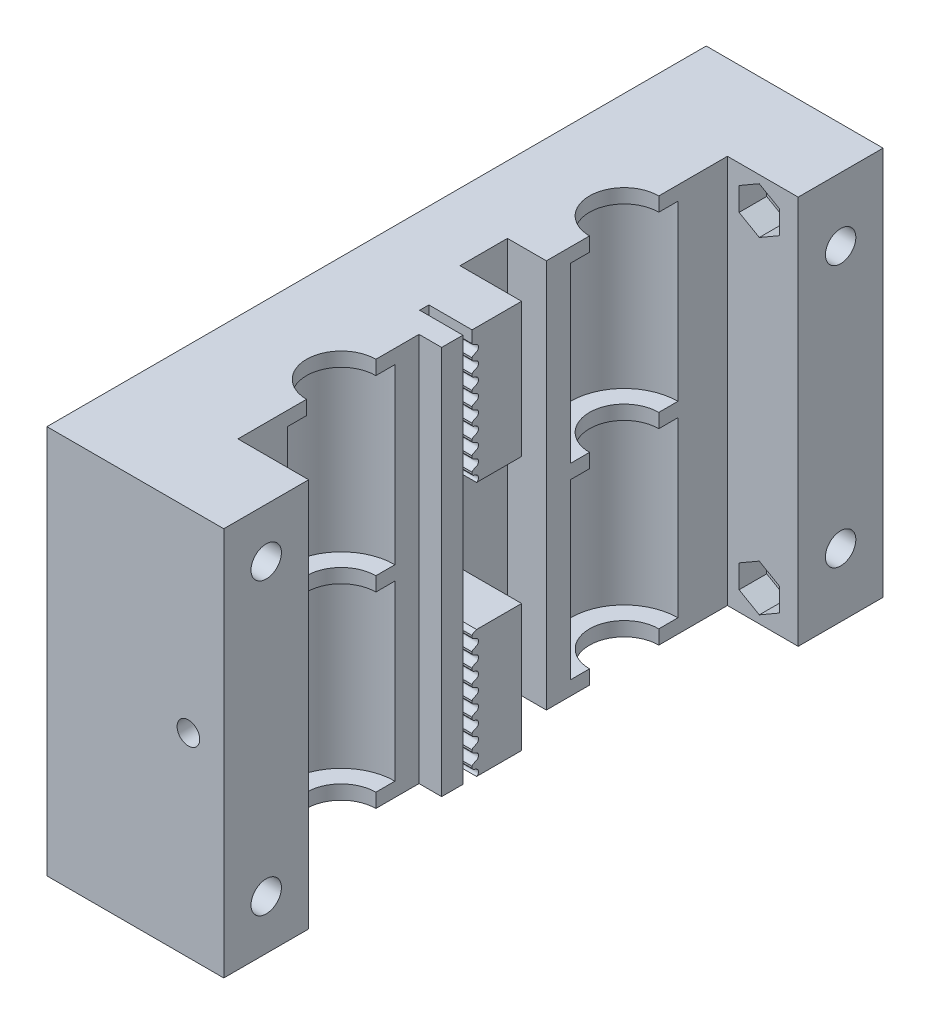
SolidWorks part; units mm, degrees
ref_plane "Front Plane" through (0, 0, 0) normal (0, 0, 1) x (1, 0, 0)
ref_plane "Top Plane" through (0, 0, 0) normal (0, 1, 0) x (1, 0, 0)
ref_plane "Right Plane" through (0, 0, 0) normal (1, 0, 0) x (0, 0, -1)
sketch "Sketch1" plane through (0, 0, 0) normal (0, 1, 0) x (1, 0, 0)
  line L0 (0, 36.6) -> (0, 43.6)
  line L1 (0, 43.6) -> (10, 43.6)
  line L2 (10, 43.6) -> (10, 55.6)
  line L3 (10, 55.6) -> (-15, 55.6)
  line L5 (-15, -37.6) -> (10, -37.6)
  line L6 (10, -37.6) -> (10, -25.6)
  line L7 (10, -25.6) -> (0, -25.6)
  line L8 (0, -25.6) -> (0, -18.6)
  line L9 (0, 21.4) -> (0, -3.4) construction
  line L10 (0, 18) -> (-5.5, 18)
  line L11 (-5.5, 18) -> (-5.5, 0)
  line L12 (-5.5, 0) -> (0, 0)
  line L24 (-15, 55.6) -> (-15, -37.6)
  line L25 (0, 0) -> (0, -3.4)
  line L26 (0, 18) -> (0, 21.4)
  arc A1 (0, 21.4) -> (0, 36.6) centre (0, 29) cw
  arc A2 (0, -18.6) -> (0, -3.4) centre (0, -11) cw
  dimension "D2" = 7.6
  dimension "D3" = 7.6
  dimension "D4" = 7
  dimension "D5" = 7
  dimension "D6" = 12
  dimension "D7" = 12
  dimension "D8" = 18
  dimension "D9" = 10
  dimension "D10" = 10
  dimension "D11" = 5.5
  dimension "D12" = 3.4
  dimension "D13" = 3.4
  dimension "D14" = 25
  dimension "D15" = 40
extrude "Boss-Extrude1" add sketch "Sketch1" along normal blind 55
sketch "Sketch2" plane through (0, 0, 0) normal (0, -1, 0) x (1, 0, 0)
  line L0 (0, 18.6) -> (0, 15.9)
  line L1 (0, 6.1) -> (0, 3.4)
  line L2 (0, -21.4) -> (0, -24.102)
  line L3 (0, -33.898) -> (0, -36.6)
  arc A0 (0, 3.4) -> (0, 18.6) centre (0, 11) cw
  arc A1 (0, 6.1) -> (0, 15.9) centre (0, 11) cw
  arc A2 (0, -36.6) -> (0, -21.4) centre (0, -29) cw
  arc A3 (0, -33.898) -> (0, -24.102) centre (0, -29) cw
  dimension "D1" = 4.9
  dimension "D2" = 4.898
extrude "Boss-Extrude2" add sketch "Sketch2" against normal blind 2
ref_plane "Plane1" through (0, 26.5, 0) normal (0, -1, 0) x (-1, 0, 0)
sketch "Sketch3" plane through (0, 26.5, 0) normal (0, -1, 0) x (-1, 0, 0)
  line L0 (0, -3.4) -> (0, -6.1)
  line L1 (0, -15.9) -> (0, -18.6)
  line L2 (0, 21.4) -> (0, 24.1)
  line L3 (0, 33.9) -> (0, 36.6)
  arc A0 (0, -18.6) -> (0, -3.4) centre (0, -11) ccw
  arc A1 (0, -15.9) -> (0, -6.1) centre (0, -11) ccw
  arc A2 (0, 36.6) -> (0, 21.4) centre (0, 29) cw
  arc A3 (0, 24.1) -> (0, 33.9) centre (0, 29) ccw
  dimension "D1" = 4.9
extrude "Boss-Extrude3" add sketch "Sketch3" against normal blind 2
ref_plane "Plane2" through (0, 53, 0) normal (0, -1, 0) x (-1, 0, 0)
sketch "Sketch4" plane through (0, 53, 0) normal (0, -1, 0) x (-1, 0, 0)
  line L0 (0, -18.6) -> (0, -15.9)
  line L1 (0, -6.1) -> (0, -3.4)
  line L2 (0, 36.6) -> (0, 33.9)
  line L3 (0, 24.1) -> (0, 21.4)
  arc A0 (0, -3.4) -> (0, -18.6) centre (0, -11) cw
  arc A1 (0, -15.9) -> (0, -6.1) centre (0, -11) ccw
  arc A2 (0, -15.9) -> (0, -6.1) centre (0, -11) ccw construction
  arc A3 (0, 21.4) -> (0, 36.6) centre (0, 29) ccw construction
  arc A5 (0, 24.1) -> (0, 33.9) centre (0, 29) ccw
  arc A6 (0, 21.4) -> (0, 36.6) centre (0, 29) ccw
  arc A7 (0, 24.1) -> (0, 33.9) centre (0, 29) ccw construction
extrude "Boss-Extrude4" add sketch "Sketch4" against normal blind 2
sketch "Sketch7" plane through (0, 55, 0) normal (0, 1, 0) x (1, 0, 0)
  line L0 (0, 0) -> (3.2, 0)
  line L1 (3.2, 0) -> (3.2, -2)
  line L2 (3.2, -2) -> (0, -2)
  line L3 (0, -6.1) -> (0, 0) construction
  line L4 (0, -2) -> (0, 0)
  dimension "D1" = 2
  dimension "D2" = 3.2
extrude "Boss-Extrude5" add sketch "Sketch7" against normal up to surface (55 mm away) up to face at (-0.6749, 0, -9)
sketch "Sketch8" plane through (0, 55, 0) normal (0, 1, 0) x (1, 0, 0)
  line L0 (0, 18) -> (0, 0) construction
  line L1 (-3.9424, 9) -> (6.0186, 9) construction
  line L2 (-5.5, 0) -> (3.2, 0)
  line L3 (3.2, 0) -> (-5.5, 0) construction
  line L4 (3.2, 0) -> (3.2, 3)
  line L5 (3.2, 3) -> (-5.5, 3)
  line L6 (-5.5, 0) -> (-5.5, 18) construction
  line L7 (-5.5, 3) -> (-5.5, 0)
  line L8 (3.2, -2) -> (3.2, 0) construction
  line L9 (-5.5, 11.3) -> (3.2, 11.3)
  line L10 (3.2, 11.3) -> (3.2, 4.3)
  line L11 (3.2, 4.3) -> (-5.5, 4.3)
  line L12 (-5.5, 4.3) -> (-5.5, 11.3)
  point P6 (0, 9)
  dimension "D1" = 3
  dimension "D2" = 7
  dimension "D3" = 1.3
extrude "Boss-Extrude6" add sketch "Sketch8" against normal up to surface (55 mm away) up to face at (-0.2443, 0, -7.7778)
sketch "Sketch11" plane through (3.2, 0, 0) normal (1, 0, 0) x (0, 0, -1)
  line L0 (1264.5675, 560.6102) -> (1262.5675, 560.6102) construction
  line L1 (4.3, 0) -> (4.3, 55) construction
  line L2 (4.2853, 45.4328) -> (4.2853, 47.4569)
  spline S0 degree 3 poles (4.2853, 47.4569) (4.284, 47.4147) (4.2867, 47.3463) (4.3158, 47.2523) (4.3712, 47.1708) (4.4771, 47.1012) (4.6041, 47.0544) (4.7214, 46.9971) (4.8254, 46.9474) (4.9241, 46.9047) (5.0186, 46.8525) (5.1086, 46.7783) (5.1561, 46.6816) (5.1905, 46.5926) (5.1913, 46.5195) (5.1931, 46.4561) (5.1891, 46.3829) (5.1871, 46.2871) (5.1399, 46.1709) (5.0494, 46.057) (4.9087, 45.9856) (4.7554, 45.916) (4.621, 45.8529) (4.5075, 45.8004) (4.4122, 45.7562) (4.3028, 45.6419) (4.2855, 45.5136) (4.2853, 45.4328) knots 0 0 0 0 0.042789 0.068472 0.09859 0.140403 0.193951 0.235463 0.272242 0.310543 0.344117 0.381404 0.42616 0.451184 0.477135 0.499165 0.515432 0.551275 0.595353 0.639476 0.695379 0.752126 0.810504 0.845135 0.878871 0.916023 1 1 1 1
  line M5 (4.3, 55) -> (4.3, 0)
  dimension "D1" = 2
extrude "Cut-Extrude4" cut sketch "Sketch11" against normal up to surface (8.7 mm away) contours S0 M5 up to face at (-5.5, 27.5, -3.65)
pattern_linear "LPattern1" count 24 spacing 2 along (0, 1, 0) count 4 spacing 2 along (0, 1, 0) of "Cut-Extrude4"
sketch "Sketch12" plane through (3.2, 0, 0) normal (1, 0, 0) x (0, 0, -1)
  line L0 (11.3, 0) -> (11.3, 55) construction
  line L1 (11.3, 36) -> (4.3, 36)
  line L2 (11.3, 36) -> (11.3, 18)
  line L3 (11.3, 18) -> (4.3, 18)
  line L4 (4.3, 36) -> (4.3, 18)
  dimension "D1" = 18
  dimension "D2" = 19
extrude "Cut-Extrude5" cut sketch "Sketch12" against normal up to surface (8.7 mm away) up to face at (-5.5, 27.5, -14.65)
sketch "Sketch13" plane through (0, 55, 0) normal (0, 1, 0) x (1, 0, 0)
  line L0 (-5.5, 3) -> (-2.9059, 3)
  line L1 (3.2, 3) -> (-5.5, 3) construction
  line L6 (-2.9059, 3) -> (-2.9059, 7.169)
  line L7 (-2.9059, 7.169) -> (-5.5, 7.169)
  line L8 (-5.5, 18) -> (-5.5, 0) construction
  line L9 (-5.5, 7.169) -> (-5.5, 3)
extrude "Boss-Extrude16" add sketch "Sketch13" against normal up to surface (55 mm away) up to face at (-0.409, 0, -8.1123)
sketch "Sketch14" plane through (0, 55, 0) normal (0, 1, 0) x (1, 0, 0)
  line L0 (0, 0) -> (0, -2)
  line L1 (0, -2) -> (3.2, -2)
  line L2 (3.2, -2) -> (3.2, 0)
  line L3 (3.2, -2) -> (3.2, 3) construction
  line L4 (3.2, 0) -> (0, 0)
extrude "Cut-Extrude6" cut sketch "Sketch14" against normal up to surface (55 mm away) up to face at (-0.1732, 0, -8.1123)
sketch "Sketch16" plane through (-2.9059, 0, 0) normal (1, 0, 0) x (0, 0, -1)
  line L0 (7.169, 36) -> (3, 36)
  line L1 (3, 0) -> (3, 55) construction
  line L2 (7.169, 18) -> (3, 18)
  line L3 (3, 18) -> (3, 36)
  line L4 (7.169, 36) -> (7.169, 18)
extrude "Cut-Extrude7" cut sketch "Sketch16" against normal up to surface (2.5941 mm away) up to face at (-5.5, 27.25, -11.9423)
sketch "Sketch17" plane through (-15, 0, 0) normal (-1, 0, 0) x (0, 0, 1)
  line L0 (-55.6, 55) -> (37.6, 55) construction
  line L1 (37.6, 55) -> (37.6, 0) construction
  line L2 (37.6, 0) -> (25.6, 0) construction
  line L3 (-36.6, 0) -> (-43.6, 0) construction
  line L4 (-55.6, 55) -> (-55.6, 0) construction
  circle A0 centre (31.6, 48) radius 2.15
  circle A1 centre (31.6, 7) radius 2.15
  circle A2 centre (-49.6, 9) radius 2.15
  circle A3 centre (-49.6, 46) radius 2.15
  dimension "D1" = 4.3
  dimension "D2" = 4.3
  dimension "D3" = 4.3
  dimension "D4" = 4.3
  dimension "D6" = 6
  dimension "D7" = 7
  dimension "D5" = 7
  dimension "D8" = 6
  dimension "D9" = 9
  dimension "D10" = 6
  dimension "D11" = 6
  dimension "D12" = 9
extrude "Cut-Extrude8" cut sketch "Sketch17" against normal up to surface (25 mm away) up to face at (10, 27.5, 31.6)
ref_plane "Plane3" through (-11.9, 0, 0) normal (-1, 0, 0) x (0, 0, 1)
sketch "Sketch20" plane through (-5.5, 0, 0) normal (1, 0, 0) x (0, 0, -1)
  line L0 (55.6, 55) -> (-37.6, 55) construction
  line L1 (55.6, 55) -> (55.6, 0) construction
  circle A0 centre (7, 27.5) radius 2.7
  dimension "D1" = 5.4
  dimension "D2" = 27.5
  dimension "D3" = 48.6
extrude "Cut-Extrude9" cut sketch "Sketch20" against normal up to surface (9.5 mm away) up to face at (-15, 46, -47.45)
sketch "Sketch21" plane through (0, 0, -43.6) normal (0, 0, 1) x (1, 0, 0)
  line L0 (10, 55) -> (10, 0) construction
  line L1 (4.5, 47.3091) -> (7.35, 48.9546)
  line L2 (7.35, 48.9546) -> (7.35, 52.2454)
  line L3 (7.35, 52.2454) -> (4.5, 53.8909)
  line L4 (4.5, 53.8909) -> (1.65, 52.2454)
  line L5 (1.65, 52.2454) -> (1.65, 48.9546)
  line L6 (1.65, 48.9546) -> (4.5, 47.3091)
  line L7 (0, 55) -> (10, 55) construction
  circle A0 centre (4.5, 50.6) radius 2.85 construction
  dimension "D2" = 4.4
  dimension "D3" = 5.5
  dimension "D1" = 5.7
ref_plane "Plane4" through (0, 27.5, 0) normal (0, 1, 0) x (1, 0, 0)
extrude "Cut-Extrude10" cut sketch "Sketch21" against normal blind 3.9
sketch "Sketch23" plane through (0, 0, -47.5) normal (0, 0, 1) x (1, 0, 0)
  line L0 (0, 55) -> (10, 55) construction
  line L1 (10, 55) -> (10, 0) construction
  circle A0 centre (4.5, 50.6) radius 1.6
  dimension "D1" = 3.2
  dimension "D2" = 4.4
  dimension "D3" = 5.5
extrude "Cut-Extrude11" cut sketch "Sketch23" against normal up to surface (8.1 mm away) up to face at (-2.5, 27.5, -55.6)
mirror "Mirror1" about plane through (0, 27.5, 0) normal (0, 1, 0) of "Cut-Extrude11", "Cut-Extrude10"
sketch "Sketch26" plane through (0, 0, 25.6) normal (0, 0, -1) x (-1, 0, 0)
  line L0 (-10, 55) -> (-10, 0) construction
  line L1 (-5, 24.2091) -> (-2.15, 25.8546)
  line L2 (-2.15, 25.8546) -> (-2.15, 29.1454)
  line L3 (-2.15, 29.1454) -> (-5, 30.7909)
  line L4 (-5, 30.7909) -> (-7.85, 29.1454)
  line L5 (-7.85, 29.1454) -> (-7.85, 25.8546)
  line L6 (-7.85, 25.8546) -> (-5, 24.2091)
  line L7 (-10, 0) -> (0, 0) construction
  circle A0 centre (-5, 27.5) radius 2.85 construction
  dimension "D1" = 27.5
  dimension "D2" = 5
  dimension "D3" = 5.7
extrude "Cut-Extrude12" cut sketch "Sketch26" against normal blind 4
sketch "Sketch27" plane through (0, 0, 29.6) normal (0, 0, -1) x (-1, 0, 0)
  line L0 (-10, 55) -> (-10, 0) construction
  line L1 (-10, 55) -> (0, 55) construction
  circle A0 centre (-5, 27.5) radius 1.6
  dimension "D3" = 3.2
  dimension "D1" = 5
  dimension "D2" = 27.5
extrude "Cut-Extrude13" cut sketch "Sketch27" against normal up to surface (8 mm away) up to face at (-2.5, 27.5, 37.6)
sketch "Sketch28" plane through (-15, 0, 0) normal (-1, 0, 0) x (0, 0, 1)
  line L0 (-55.6, 55) -> (-55.6, 0) construction
  line L1 (-45.95, 11.1073) -> (-49.6, 13.2147)
  line L2 (-49.6, 13.2147) -> (-53.25, 11.1073)
  line L3 (-53.25, 11.1073) -> (-53.25, 6.8927)
  line L4 (-53.25, 6.8927) -> (-49.6, 4.7853)
  line L5 (-49.6, 4.7853) -> (-45.95, 6.8927)
  line L6 (-45.95, 6.8927) -> (-45.95, 11.1073)
  circle A0 centre (-49.6, 9) radius 3.65 construction
  dimension "D1" = 7.3
extrude "Cut-Extrude14" cut sketch "Sketch28" against normal blind 4
pattern_linear "LPattern4" count 2 spacing 37 along (0, 1, 0) of "Cut-Extrude14"
sketch "Sketch29" plane through (-15, 0, 0) normal (-1, 0, 0) x (0, 0, 1)
  line L0 (37.6, 55) -> (37.6, 0) construction
  line L1 (31.6, 11.2147) -> (27.95, 9.1073)
  line L2 (27.95, 9.1073) -> (27.95, 4.8927)
  line L3 (27.95, 4.8927) -> (31.6, 2.7853)
  line L4 (31.6, 2.7853) -> (35.25, 4.8927)
  line L5 (35.25, 4.8927) -> (35.25, 9.1073)
  line L6 (35.25, 9.1073) -> (31.6, 11.2147)
  circle A0 centre (31.6, 7) radius 3.65 construction
  point P11 (35.25, 7)
  dimension "D1" = 7.3
extrude "Cut-Extrude15" cut sketch "Sketch29" against normal blind 4
pattern_linear "LPattern5" count 2 spacing 41 along (0, 1, 0) of "Cut-Extrude15"
ref_plane "Plane5" through (0, 0, -53.7) normal (0, 0, -1) x (-1, 0, 0)
